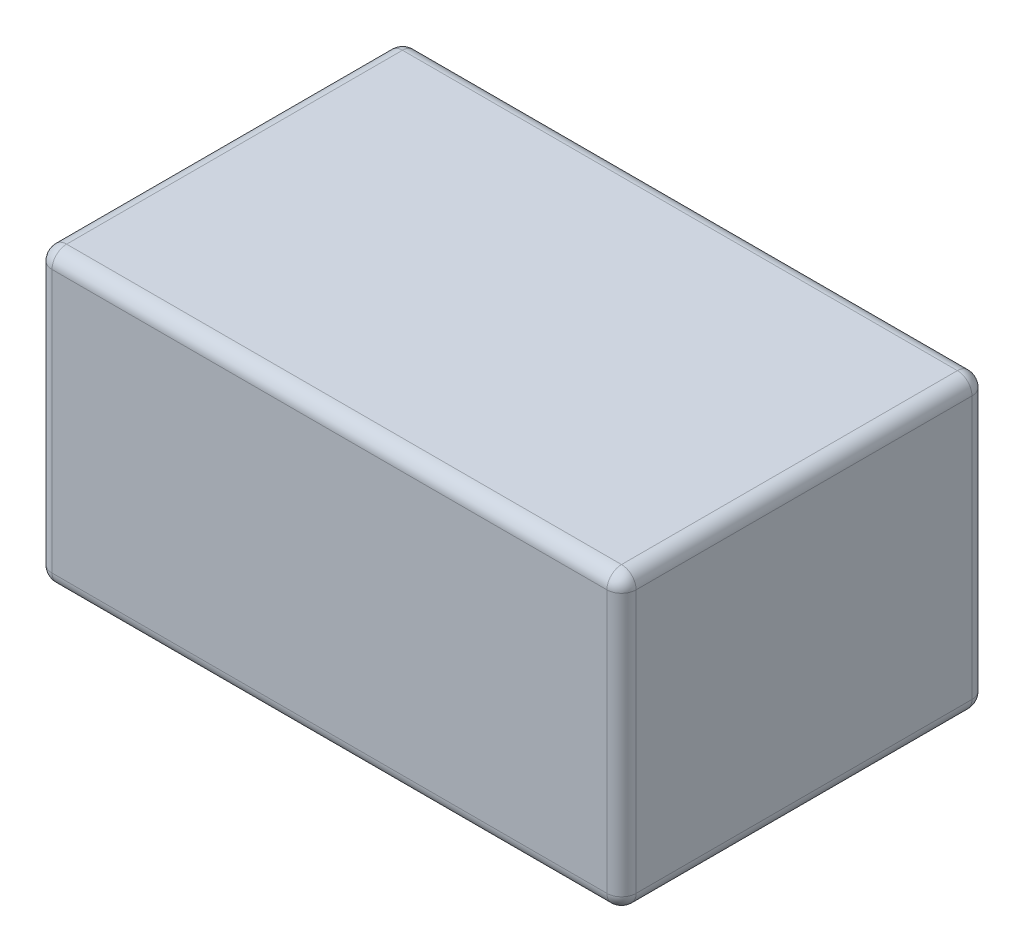
SolidWorks part; units mm, degrees
material "聚脂树脂"
ref_plane "前视基准面" through (0, 0, 0) normal (0, 0, 1) x (1, 0, 0)
ref_plane "上视基准面" through (0, 0, 0) normal (0, 1, 0) x (1, 0, 0)
ref_plane "右视基准面" through (0, 0, 0) normal (1, 0, 0) x (0, 0, -1)
sketch "草图1" plane through (0, 0, 0) normal (0, 1, 0) x (1, 0, 0)
  line L1 (-40, 25) -> (40, 25)
  line L2 (-40, 25) -> (-40, -25)
  line L3 (-40, -25) -> (40, -25)
  line L4 (40, 25) -> (40, -25)
  line L5 (-40, 25) -> (40, -25) construction
  line L6 (-40, -25) -> (40, 25) construction
  point P0 (0, 0)
  dimension "D1" = 50
  dimension "D2" = 80
extrude "凸台-拉伸1" add sketch "草图1" along normal blind 40
fillet "圆角1" radius 2 12 edges at (40, 20, -25) (0, 0, -25) (40, 0, 0) (-40, 20, -25) (-40, 0, 0) (-40, 20, 25) (40, 20, 25) (0, 0, 25) (0, 40, 25) (-40, 40, 0) (0, 40, -25) (40, 40, 0)
